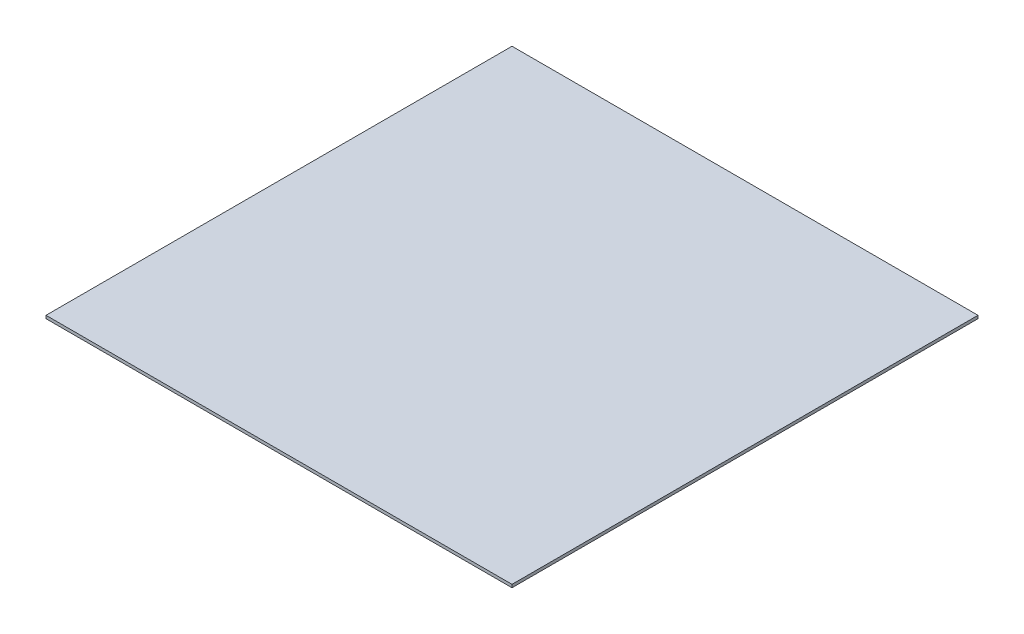
SolidWorks part; units mm, degrees
ref_plane "Front Plane" through (0, 0, 0) normal (0, 0, 1) x (1, 0, 0)
ref_plane "Top Plane" through (0, 0, 0) normal (0, 1, 0) x (1, 0, 0)
ref_plane "Right Plane" through (0, 0, 0) normal (1, 0, 0) x (0, 0, -1)
sketch "Sketch1" plane through (0, 0, 0) normal (0, 1, 0) x (1, 0, 0)
  line L1 (1648.2525, -154.7157) -> (1178.3525, -154.7157)
  line L2 (1648.2525, -154.7157) -> (1648.2525, 315.1843)
  line L3 (1648.2525, 315.1843) -> (1178.3525, 315.1843)
  line L4 (1178.3525, -154.7157) -> (1178.3525, 315.1843)
  dimension "D1" = 469.9
  dimension "D2" = 469.9
extrude "Boss-Extrude1" add sketch "Sketch1" along normal blind 3
